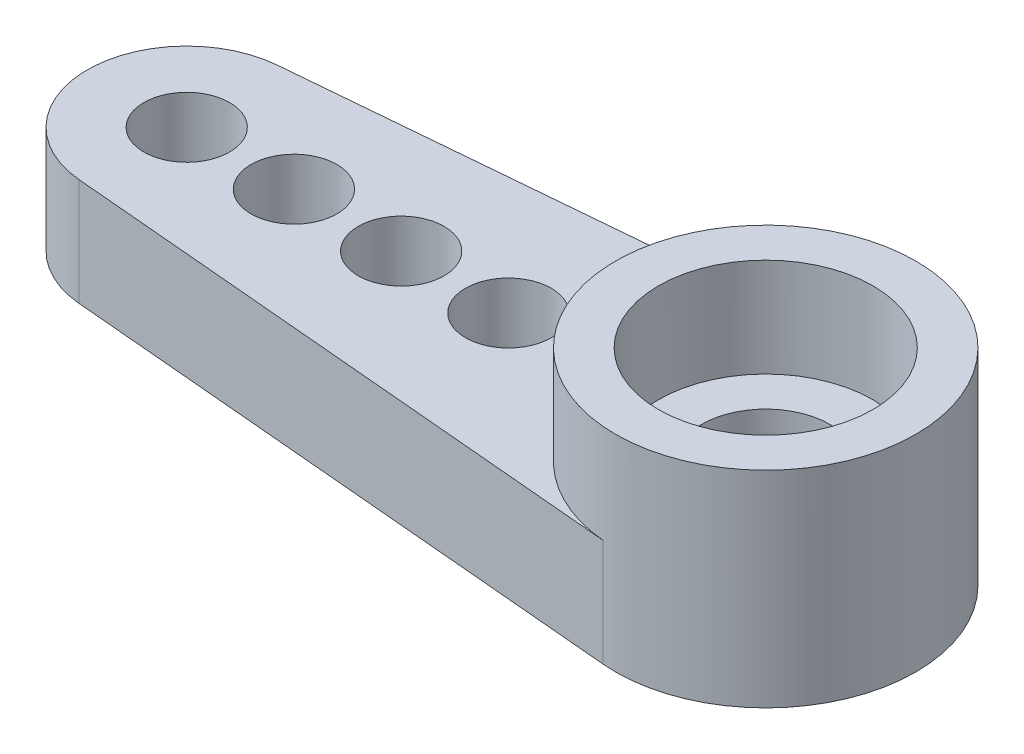
SolidWorks part; units mm, degrees
material "1060 合金"
ref_plane "前视基准面" through (0, 0, 0) normal (0, 0, 1) x (1, 0, 0)
ref_plane "上视基准面" through (0, 0, 0) normal (0, 1, 0) x (1, 0, 0)
ref_plane "右视基准面" through (0, 0, 0) normal (1, 0, 0) x (0, 0, -1)
other "Configuration Table"
sketch "草图1" plane through (0, 0, 0) normal (0, 1, 0) x (1, 0, 0)
  circle A0 centre (0, 0) radius 2.5
  circle A1 centre (0, 0) radius 3.5
  dimension "D1" = 5
  dimension "D2" = 7
extrude "凸台-拉伸1" add sketch "草图1" along normal blind 4.8
sketch "草图2" plane through (0, 0, 0) normal (0, -1, 0) x (1, 0, 0)
  line L0 (0, 0) -> (-11.041, 0) construction
  line L1 (-13.7028, 2.3111) -> (-0.3059, 3.4866)
  line L2 (-13.7028, -2.3111) -> (-0.3059, -3.4866)
  circle A0 centre (0, 0) radius 3.5 construction
  circle A1 centre (-13.5, 0) radius 2.32 construction
  arc A2 (-13.7028, 2.3111) -> (-13.7028, -2.3111) centre (-13.5, 0) ccw
  arc A3 (-0.3059, 3.4866) -> (-0.3059, -3.4866) centre (0, 0) cw
  circle A4 centre (0, 0) radius 1.5
  circle A5 centre (-13.5, 0) radius 1
  circle A6 centre (-11, 0) radius 1
  circle A7 centre (-8.5, 0) radius 1
  circle A8 centre (-6, 0) radius 1
  dimension "D1" = 7
  dimension "D2" = 4.64
  dimension "D4" = 2
  dimension "D5" = 2
  dimension "D6" = 2
  dimension "D7" = 2
  dimension "D8" = 6
  dimension "D9" = 8.5
  dimension "D10" = 3
  dimension "D11" = 11
  dimension "D3" = 13.5
extrude "凸台-拉伸2" add sketch "草图2" against normal blind 2.5
